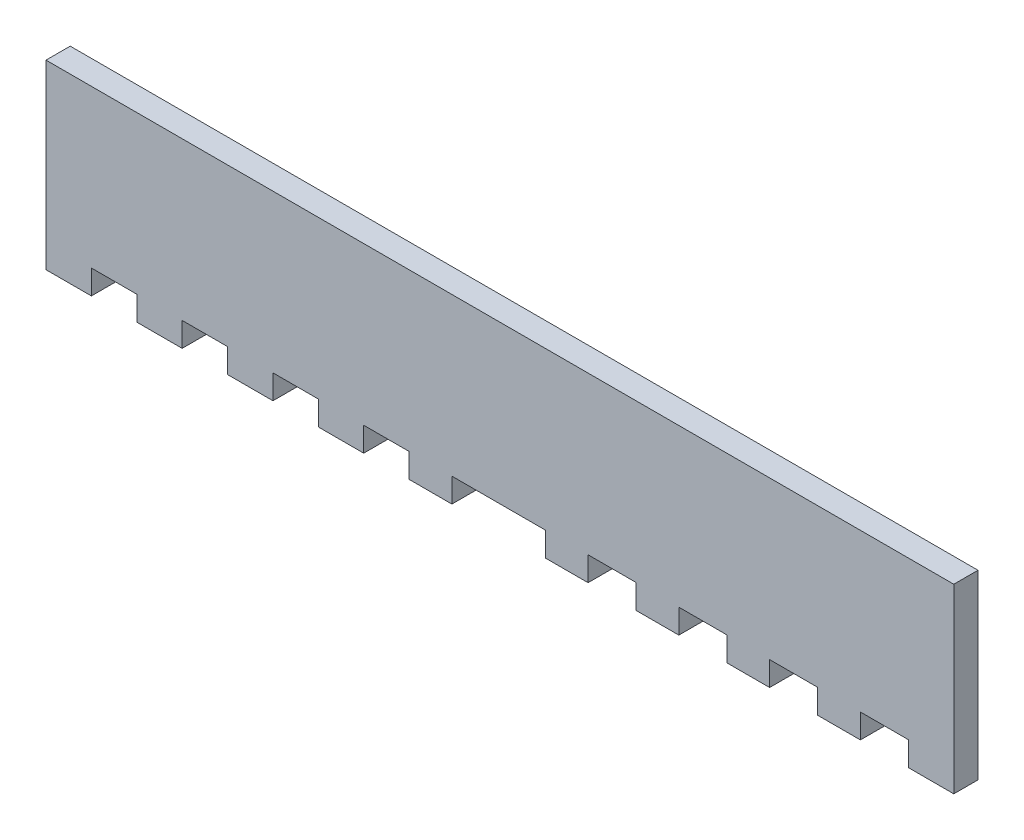
SolidWorks part; units mm, degrees
ref_plane "Plan de face" through (0, 0, 0) normal (0, 0, 1) x (1, 0, 0)
ref_plane "Plan de dessus" through (0, 0, 0) normal (0, 1, 0) x (1, 0, 0)
ref_plane "Plan de droite" through (0, 0, 0) normal (1, 0, 0) x (0, 0, -1)
sketch "Esquisse1" plane through (0, 0, 0) normal (0, 0, 1) x (1, 0, 0)
  line L1 (-150, -30) -> (150, -30)
  line L2 (-150, -30) -> (-150, 30)
  line L3 (-150, 30) -> (150, 30)
  line L4 (150, -30) -> (150, 30)
  line L5 (-150, -30) -> (150, 30) construction
  line L6 (-150, 30) -> (150, -30) construction
  point P0 (0, 0)
  dimension "D1" = 300
  dimension "D2" = 60
extrude "Boss.-Extru.1" add sketch "Esquisse1" along normal blind 8
sketch "Esquisse2" plane through (0, 0, 0) normal (0, 0, 1) x (1, 0, 0)
  line L1 (-150, -30) -> (150, -30) construction
  line L2 (-0.863, -30) -> (15, -30)
  line L4 (-0.863, -22) -> (15, -22)
  line L5 (15, -30) -> (15, -22)
  line L6 (29.137, -30) -> (29.137, -22)
  line L7 (29.137, -30) -> (45, -30)
  line L8 (45, -30) -> (45, -22)
  line L9 (29.137, -22) -> (45, -22)
  line L10 (59.137, -30) -> (59.137, -22)
  line L11 (59.137, -30) -> (75, -30)
  line L12 (75, -30) -> (75, -22)
  line L13 (59.137, -22) -> (75, -22)
  line L14 (89.137, -30) -> (89.137, -22)
  line L15 (89.137, -30) -> (105, -30)
  line L16 (105, -30) -> (105, -22)
  line L17 (89.137, -22) -> (105, -22)
  line L18 (119.137, -30) -> (119.137, -22)
  line L19 (119.137, -30) -> (135, -30)
  line L20 (135, -30) -> (135, -22)
  line L21 (119.137, -22) -> (135, -22)
  line L22 (-120, -30) -> (-135, -30)
  line L23 (-135, -30) -> (-135, -22)
  line L24 (-120, -22) -> (-135, -22)
  line L25 (-120, -30) -> (-120, -22)
  line L26 (-90, -30) -> (-105, -30)
  line L27 (-105, -30) -> (-105, -22)
  line L28 (-90, -22) -> (-105, -22)
  line L29 (-90, -30) -> (-90, -22)
  line L30 (-60, -30) -> (-75, -30)
  line L31 (-75, -30) -> (-75, -22)
  line L32 (-60, -22) -> (-75, -22)
  line L33 (-60, -30) -> (-60, -22)
  line L34 (-30, -30) -> (-45, -30)
  line L35 (-45, -30) -> (-45, -22)
  line L36 (-30, -22) -> (-45, -22)
  line L37 (-30, -30) -> (-30, -22)
  line L39 (-0.863, -30) -> (-15.863, -30)
  line L41 (-0.863, -22) -> (-15.863, -22)
  line L42 (-15.863, -30) -> (-15.863, -22)
  dimension "D1" = 15
  dimension "D2" = 8
  dimension "D3" = 5
extrude "Enlèv. mat.-Extru.1" cut sketch "Esquisse2" along normal blind 8
